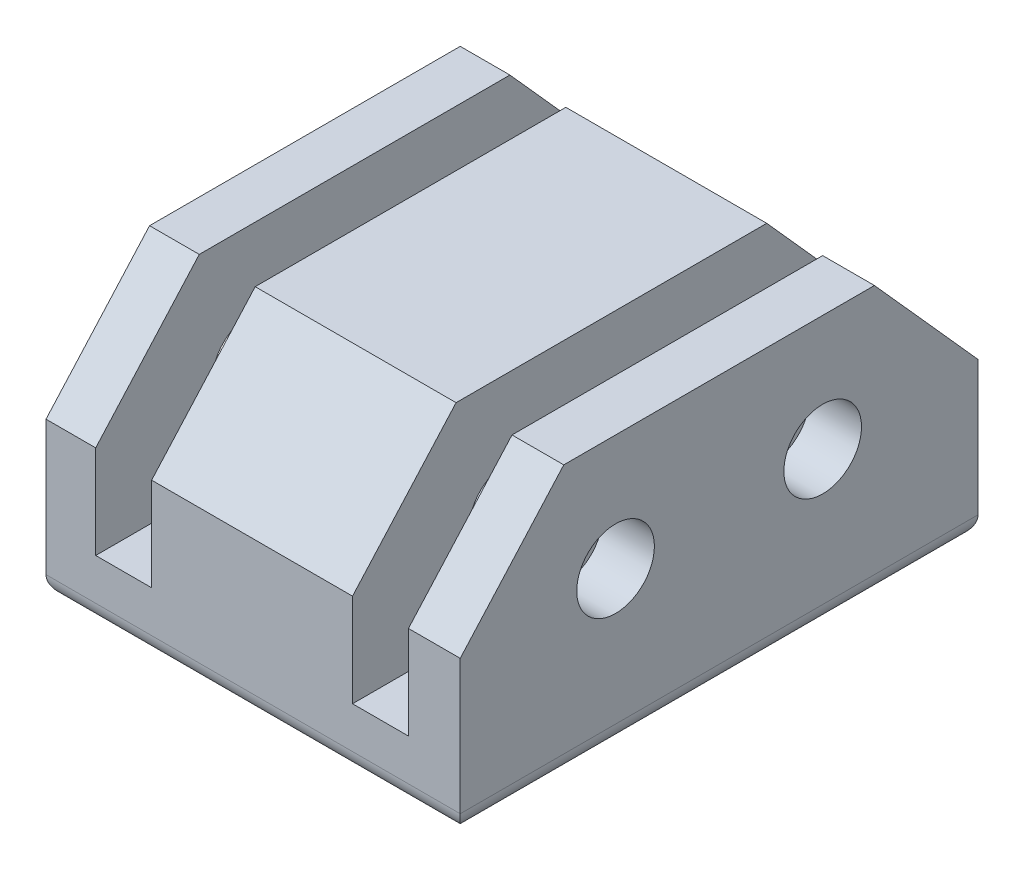
SolidWorks part; units mm, degrees
ref_plane "Front Plane" through (0, 0, 0) normal (0, 0, 1) x (1, 0, 0)
ref_plane "Top Plane" through (0, 0, 0) normal (0, 1, 0) x (1, 0, 0)
ref_plane "Right Plane" through (0, 0, 0) normal (1, 0, 0) x (0, 0, -1)
sketch "Sketch1" plane through (0, 0, 0) normal (1, 0, 0) x (0, 0, -1)
  line L1 (0, 0) -> (63.5, 0)
  line L2 (0, 0) -> (0, 6.35)
  line L3 (0, 6.35) -> (63.5, 6.35)
  line L4 (63.5, 0) -> (63.5, 6.35)
  dimension "D1" = 6.35
  dimension "D2" = 63.5
extrude "Boss-Extrude1" add sketch "Sketch1" against normal blind 50.8
sketch "Sketch2" plane through (0, 0, 0) normal (1, 0, 0) x (0, 0, -1)
  line L0 (0, 6.35) -> (0, 19.05)
  line L1 (0, 19.05) -> (12.7, 33.249)
  line L2 (12.7, 33.249) -> (50.8, 33.249)
  line L3 (50.8, 33.249) -> (63.5, 19.05)
  line L4 (63.5, 19.05) -> (63.5, 6.35)
  line L5 (63.5, 6.35) -> (0, 6.35)
  point P7 (31.75, 33.249)
  point P10 (31.75, 6.35)
  dimension "D1" = 38.1
  dimension "D2" = 12.7
  dimension "D3" = 12.7
  dimension "D4" = 19.05
  dimension "D5" = 19.05
extrude "Boss-Extrude2" add sketch "Sketch2" against normal blind 50.8
sketch "Sketch10" plane through (0, 0, -63.5) normal (0, 0, -1) x (-1, 0, 0)
  line L1 (50.8, 33.249) -> (0, 33.249) construction
  line L3 (6.35, 7.62) -> (6.35, 33.249)
  line L4 (6.35, 33.249) -> (13.208, 33.249)
  line L5 (13.208, 7.62) -> (13.208, 33.249)
  line L6 (6.35, 7.62) -> (13.208, 7.62)
  line L8 (50.8, 0) -> (0, 0) construction
  point P11 (13.208, 7.62)
  dimension "D1" = 7.62
  dimension "D2" = 6.858
  dimension "D3" = 6.35
extrude "Cut-Extrude1" cut sketch "Sketch10" against normal through all
pattern_linear "LPattern3" count 2 spacing 31.496 along (-1, 0, 0) of "Cut-Extrude1"
sketch "Sketch11" plane through (0, 0, 0) normal (1, 0, 0) x (0, 0, -1)
  circle A0 centre (19.05, 19.05) radius 4.7625
  circle A1 centre (19.05, 19.05) radius 7.9375 construction
  circle A2 centre (44.45, 19.05) radius 4.7625
  circle A3 centre (44.45, 19.05) radius 7.9375 construction
  dimension "D1" = 9.525
  dimension "D3" = 15.875
  dimension "D4" = 9.525
  dimension "D6" = 15.875
  dimension "D2" = 6.35
  dimension "D5" = 6.35
extrude "Cut-Extrude2" cut sketch "Sketch11" against normal through all
sketch "Sketch14" plane through (0, 33.249, 0) normal (0, 1, 0) x (1, 0, 0)
  line L3 (-37.846, 12.7) -> (-37.846, 50.8) construction
  point P0 (-25.4, 31.75)
  point P4 (-37.846, 31.75)
  dimension "D1" = 12.446
sketch "Sketch17" plane through (0, 40.0201, -44.7438) normal (0, 0.6667, -0.7454) x (-1, 0, 0)
  line L0 (13.208, -28.1343) -> (13.208, -9.0843) construction
  line L1 (37.846, -9.0843) -> (13.208, -9.0843) construction
  point P0 (25.527, -18.6093)
  point P4 (13.208, -18.6093)
  point P7 (25.527, -9.0843)
sketch "Sketch18" plane through (0, 8.4667, 9.466) normal (0, 0.6667, 0.7454) x (1, 0, 0)
  line L0 (-13.208, 33.249) -> (-13.208, 14.199) construction
  line L1 (-37.846, 33.249) -> (-13.208, 33.249) construction
  point P0 (-25.527, 23.724)
  point P1 (-25.527, 23.724)
  point P4 (-13.208, 23.724)
  point P7 (-25.527, 33.249)
ref_plane "Plane2" through (0, 33.02, 0) normal (0, -1, 0) x (-1, 0, 0)
ref_plane "midplane" through (0, 0, -31.75) normal (0, 0, -1) x (-1, 0, 0)
fillet "Fillet1" radius 2.54 4 edges at (0, 0, -31.75) (-25.4, 0, -63.5) (-50.8, 0, -31.75) (-25.4, 0, 0)
sketch "Sketch19" plane through (0, 0, 0) normal (0, -1, 0) x (1, 0, 0)
  line L0 (-25.4, -63.5) -> (-25.4, 0) construction
  line L1 (0, -63.5) -> (-50.8, -63.5) construction
  line L2 (-50.8, 0) -> (0, 0) construction
  line L3 (0, -31.75) -> (-50.8, -31.75) construction
  line L4 (0, 0) -> (0, -63.5) construction
  line L5 (-50.8, -63.5) -> (-50.8, 0) construction
  line L7 (-9.525, -50.8) -> (-41.275, -50.8) construction
  line L8 (-9.525, -50.8) -> (-9.525, -12.7) construction
  line L9 (-9.525, -12.7) -> (-41.275, -12.7) construction
  line L10 (-41.275, -50.8) -> (-41.275, -12.7) construction
  line L11 (-9.525, -50.8) -> (-41.275, -12.7) construction
  line L12 (-9.525, -12.7) -> (-41.275, -50.8) construction
  circle A0 centre (-9.525, -50.8) radius 1.778
  circle A1 centre (-41.275, -50.8) radius 1.778
  circle A2 centre (-41.275, -12.7) radius 1.778
  circle A3 centre (-9.525, -12.7) radius 1.778
  point P12 (-25.4, -31.75)
  dimension "D3" = 3.556
  dimension "D1" = 31.75
  dimension "D2" = 38.1
extrude "Cut-Extrude3" cut sketch "Sketch19" against normal up to surface (7.62 mm away) up to face at (-9.779, 7.62, -31.75)
